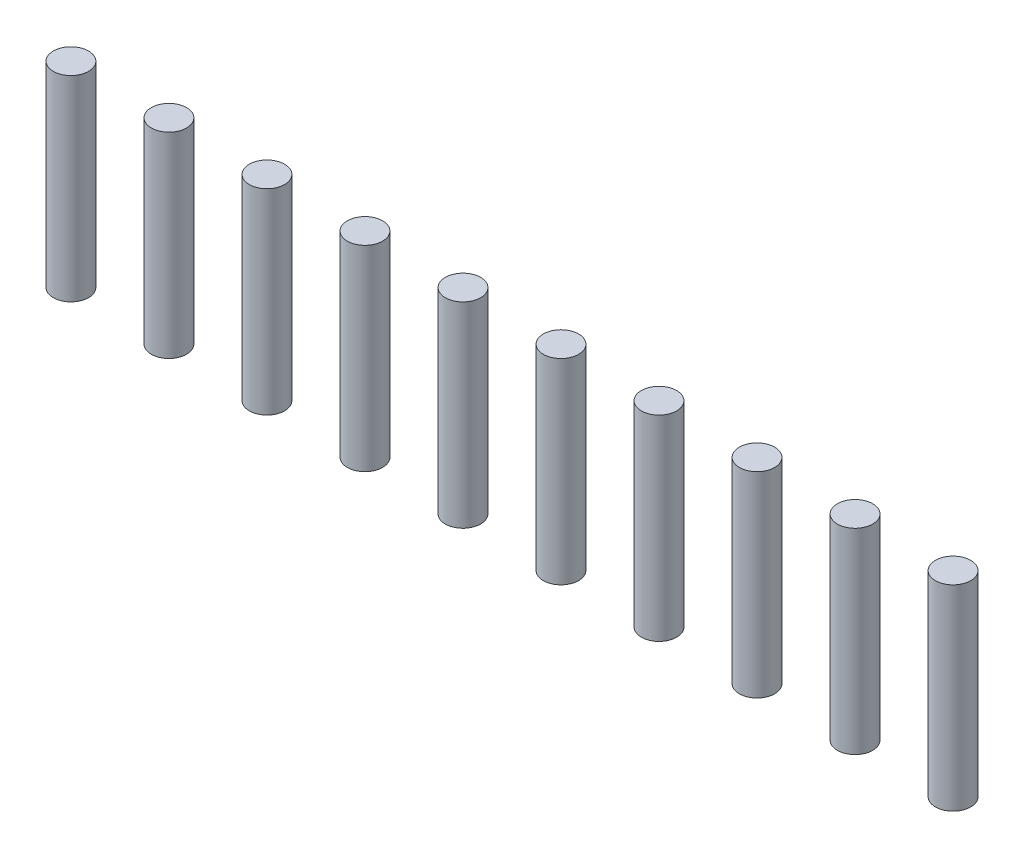
SolidWorks part; units mm, degrees
ref_plane "前视基准面" through (0, 0, 0) normal (0, 0, 1) x (1, 0, 0)
ref_plane "上视基准面" through (0, 0, 0) normal (0, 1, 0) x (1, 0, 0)
ref_plane "右视基准面" through (0, 0, 0) normal (1, 0, 0) x (0, 0, -1)
other "Configuration Table"
sketch "草图1" plane through (0, 0, 0) normal (0, 1, 0) x (1, 0, 0)
  line L0 (5, 10.0674) -> (5, -11.0462) construction
  circle A0 centre (0, 0) radius 1.8
  circle A1 centre (10, 0) radius 1.8
  circle A2 centre (20, 0) radius 1.8
  circle A3 centre (30, 0) radius 1.8
  circle A4 centre (40, 0) radius 1.8
  circle A5 centre (50, 0) radius 1.8
  circle A6 centre (60, 0) radius 1.8
  circle A7 centre (70, 0) radius 1.8
  circle A8 centre (80, 0) radius 1.8
  circle A9 centre (90, 0) radius 1.8
  dimension "D1" = 3.6
  dimension "D2" = 5
  dimension "D3" = 10
extrude "凸台-拉伸1" add sketch "草图1" along normal blind 20
